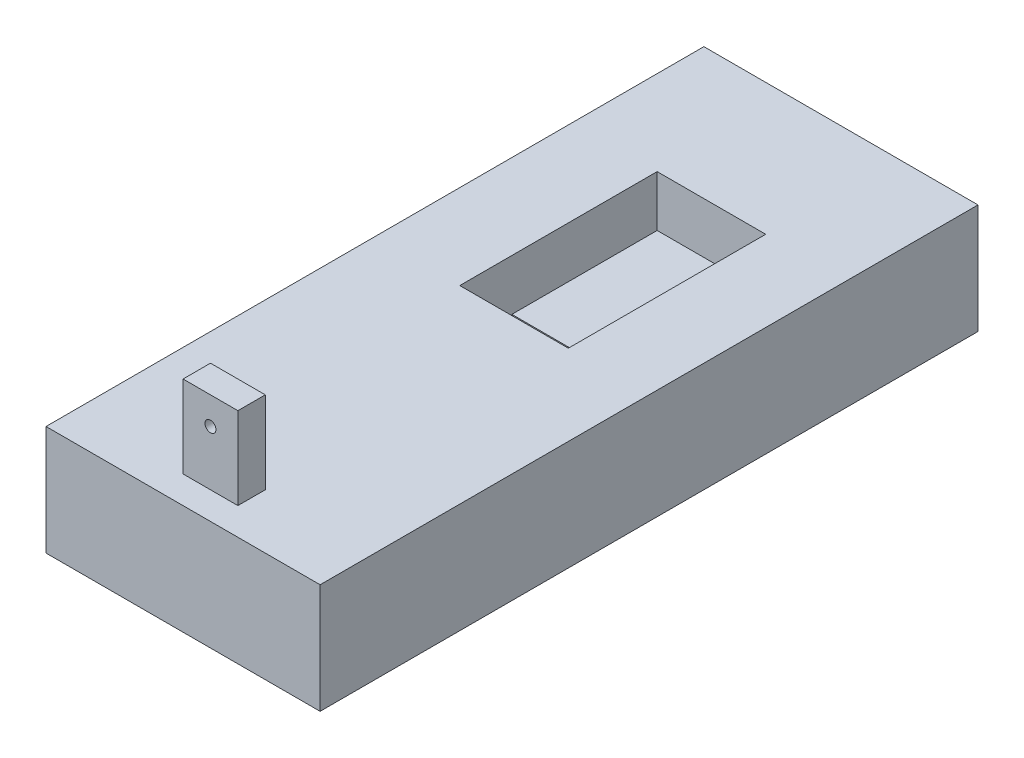
SolidWorks part; units mm, degrees
ref_plane "Front Plane" through (0, 0, 0) normal (0, 0, 1) x (1, 0, 0)
ref_plane "Top Plane" through (0, 0, 0) normal (0, 1, 0) x (1, 0, 0)
ref_plane "Right Plane" through (0, 0, 0) normal (1, 0, 0) x (0, 0, -1)
sketch "Sketch1" plane through (0, 0, 0) normal (0, 1, 0) x (1, 0, 0)
  line L0 (-28.7064, 114.1811) -> (21.2936, 114.1811)
  line L1 (21.2936, 114.1811) -> (21.2936, -5.8189)
  line L2 (-28.7064, 114.1811) -> (-28.7064, -5.8189)
  line L3 (-28.7064, -5.8189) -> (21.2936, -5.8189)
  dimension "D1" = 120
  dimension "D2" = 50
extrude "Boss-Extrude1" add sketch "Sketch1" along normal blind 20
sketch "Sketch11" plane through (0, 20, 0) normal (0, 1, 0) x (1, 0, 0)
  line L0 (21.2936, -5.8189) -> (-28.7064, -5.8189)
  line L1 (-3.7064, -0.8189) -> (-3.7064, 4.1811)
  line L3 (1.2936, -0.8189) -> (-8.7064, -0.8189)
  line L4 (1.2936, -0.8189) -> (1.2936, 4.1811)
  line L5 (-8.7064, -0.8189) -> (-8.7064, 4.1811)
  line L6 (1.2936, 4.1811) -> (-8.7064, 4.1811)
  line L7 (21.2936, 4.1811) -> (-28.7064, 4.1811) construction
  line L8 (21.2936, -0.8189) -> (-28.7064, -0.8189) construction
  line L9 (-8.7064, -5.8189) -> (-8.7064, 74.1811) construction
  line L10 (-3.7064, -5.8189) -> (-3.7064, 74.1811) construction
  line L11 (1.2936, -5.8189) -> (1.2936, 74.1811) construction
  dimension "D1" = 5
  dimension "D2" = 5
  dimension "D3" = 5
  dimension "D4" = 5
extrude "Boss-Extrude5" add sketch "Sketch11" along normal blind 15 contours L3 L5 L6 L4
sketch "Sketch13" plane through (0, 0, -4.1811) normal (0, 0, -1) x (-1, 0, 0)
  line L0 (-1.2936, 20) -> (8.7064, 20) construction
  circle A0 centre (3.7064, 30) radius 1
  dimension "D1" = 2
  dimension "D2" = 10
extrude "Cut-Extrude3" cut sketch "Sketch13" against normal blind 10 contours A0
sketch "Sketch14" plane through (0, 20, 0) normal (0, 1, 0) x (1, 0, 0)
  line L0 (-3.7064, 4.1811) -> (-3.7064, 54.1811) construction
  line L1 (1.2936, 4.1811) -> (-8.7064, 4.1811) construction
  line L3 (6.5686, 54.1811) -> (-13.2314, 54.1811)
  line L4 (6.5686, 54.1811) -> (6.5686, 90.1811)
  line L5 (6.5686, 90.1811) -> (-13.2314, 90.1811)
  line L6 (-13.2314, 54.1811) -> (-13.2314, 90.1811)
  dimension "D1" = 50
  dimension "D2" = 36
  dimension "D3" = 19.8
extrude "Cut-Extrude4" cut sketch "Sketch14" against normal blind 9.3
sketch "Sketch15" plane through (0, 10.7, 0) normal (0, 1, 0) x (1, 0, 0)
  line L0 (-13.2314, 90.1811) -> (-13.2314, 54.1811) construction
  line L1 (-13.2314, 61.1811) -> (6.5686, 61.1811)
  line L2 (-13.2314, 61.1811) -> (-13.2314, 63.6811)
  line L3 (-13.2314, 63.6811) -> (6.5686, 63.6811)
  line L4 (6.5686, 61.1811) -> (6.5686, 63.6811)
  line L5 (6.5686, 54.1811) -> (6.5686, 90.1811) construction
  line L6 (6.5686, 90.1811) -> (-13.2314, 90.1811) construction
  dimension "D1" = 26.5
  dimension "D2" = 2.5
extrude "Cut-Extrude5" cut sketch "Sketch15" against normal blind 7.1
